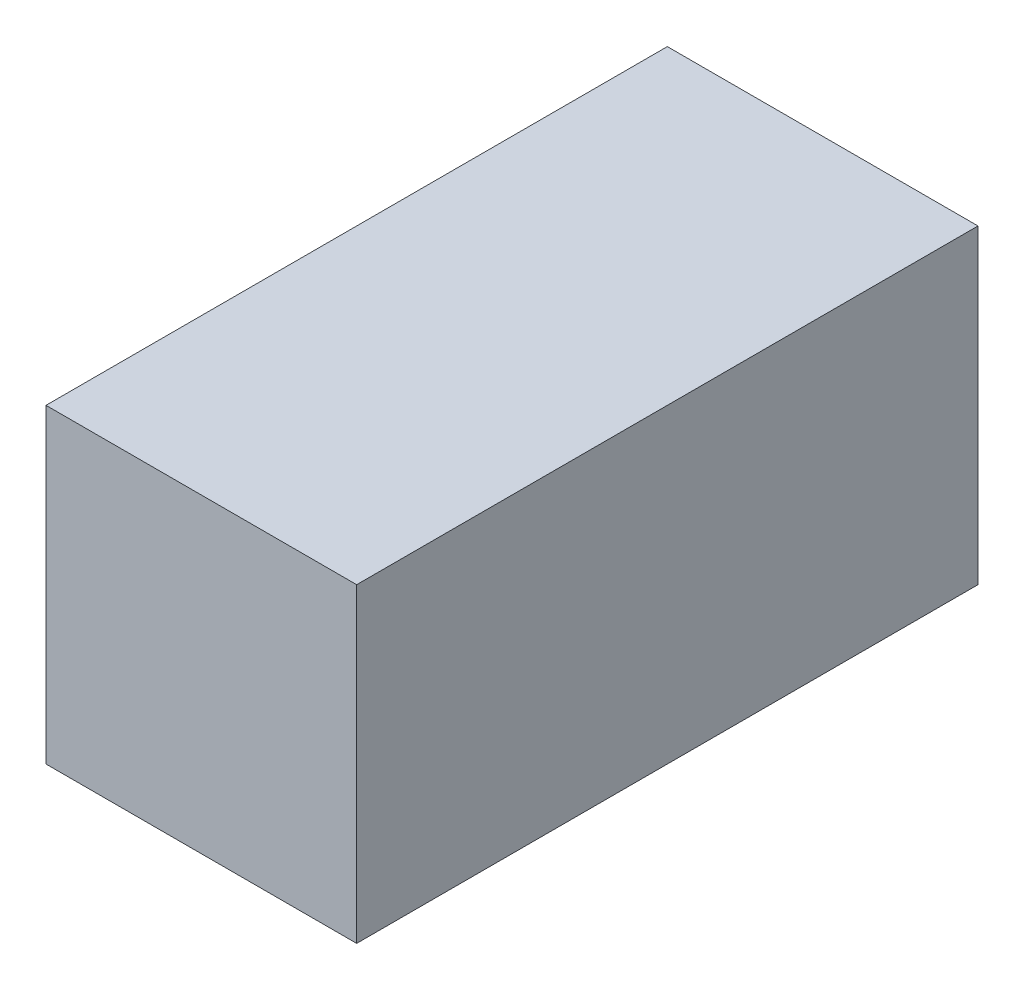
SolidWorks part; units mm, degrees
ref_plane "Front Plane" through (0, 0, 0) normal (0, 0, 1) x (1, 0, 0)
ref_plane "Top Plane" through (0, 0, 0) normal (0, 1, 0) x (1, 0, 0)
ref_plane "Right Plane" through (0, 0, 0) normal (1, 0, 0) x (0, 0, -1)
sketch "Sketch1" plane through (0, 0, 0) normal (0, 1, 0) x (1, 0, 0)
  line L1 (-5, 10) -> (5, 10)
  line L2 (-5, 10) -> (-5, -10)
  line L3 (-5, -10) -> (5, -10)
  line L4 (5, 10) -> (5, -10)
  line L5 (-5, 10) -> (5, -10) construction
  line L6 (-5, -10) -> (5, 10) construction
  point P0 (0, 0)
extrude "Boss-Extrude1" add sketch "Sketch1" along normal blind 10
sketch "Sketch2" plane through (0, 0, -10) normal (0, 0, -1) x (-1, 0, 0)
  circle A0 centre (0, 5) radius 2.5
extrude "Cut-Extrude1" cut sketch "Sketch2" against normal blind 4
